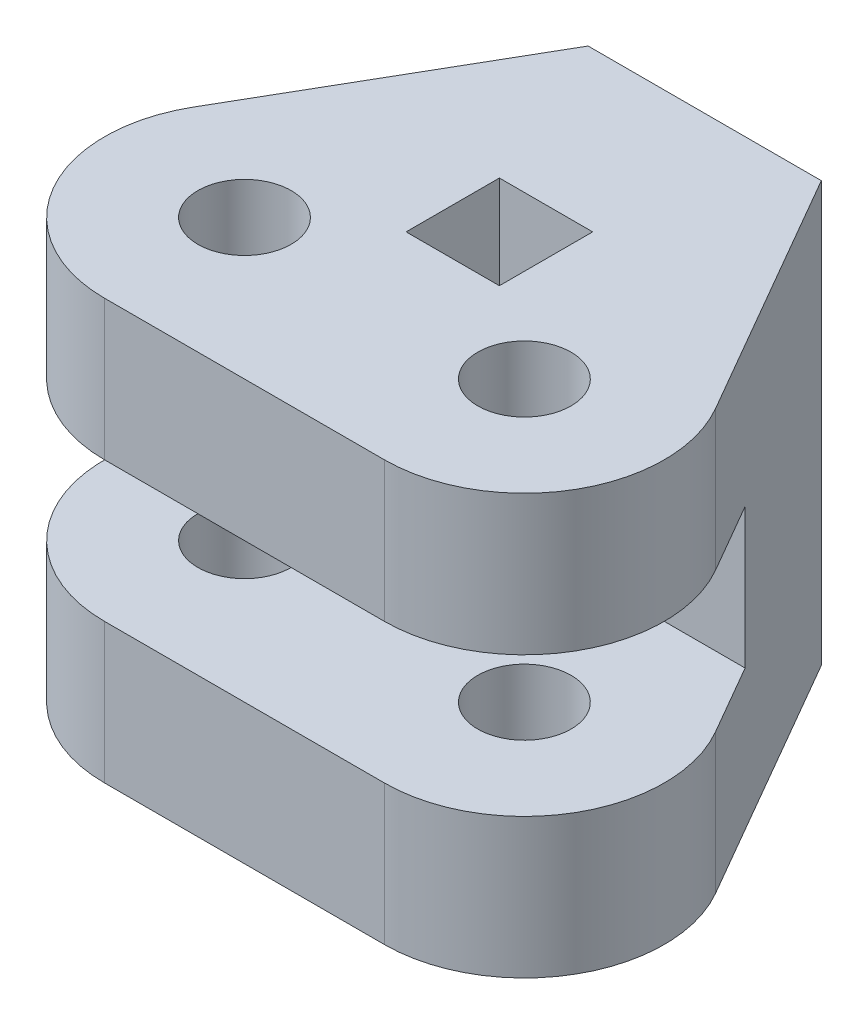
SolidWorks part; units mm, degrees
ref_plane "Alzado" through (0, 0, 0) normal (0, 0, 1) x (1, 0, 0)
ref_plane "Planta" through (0, 0, 0) normal (0, 1, 0) x (1, 0, 0)
ref_plane "Vista lateral" through (0, 0, 0) normal (1, 0, 0) x (0, 0, -1)
sketch "Croquis1" plane through (0, 0, 0) normal (0, 1, 0) x (1, 0, 0)
  line L0 (5.5981, -3.6962) -> (2.5, 1.6699)
  line L1 (-2.5, 1.6699) -> (-5.5981, -3.6962)
  line L2 (-3, -8.1962) -> (3, -8.1962)
  line L3 (0, 0) -> (-3, -5.1962) construction
  line L4 (-3, -5.1962) -> (3, -5.1962) construction
  line L5 (3, -5.1962) -> (0, 0) construction
  line L6 (8.1962, -8.1962) -> (0, 6) construction
  line L7 (-8.1962, -8.1962) -> (8.1962, -8.1962) construction
  line L8 (0, 6) -> (-8.1962, -8.1962) construction
  line L9 (-2.5, 1.6699) -> (2.5, 1.6699)
  line L10 (-1, -1.7321) -> (1, -1.7321)
  line L11 (1, -1.7321) -> (1, -3.7321)
  line L12 (1, -3.7321) -> (-1, -3.7321)
  line L13 (-1, -3.7321) -> (-1, -1.7321)
  circle A1 centre (-3, -5.1962) radius 1
  circle A2 centre (3, -5.1962) radius 1
  arc A3 (5.5981, -3.6962) -> (3, -8.1962) centre (3, -5.1962) cw
  arc A5 (-5.5981, -3.6962) -> (-3, -8.1962) centre (-3, -5.1962) ccw
  dimension "D1" = 2
  dimension "D4" = 3
  dimension "D2" = 6
  dimension "D5" = 5
  dimension "D6" = 2
  dimension "D7" = 2
  dimension "D3" = 3
extrude "Saliente-Extruir1" add sketch "Croquis1" along normal blind 9
sketch "Croquis2" plane through (0, 0, 8.1962) normal (0, 0, 1) x (1, 0, 0)
  line L0 (-3, 9) -> (3, 9) construction
  line L1 (-6, 6) -> (6, 6)
  line L2 (-6, 6) -> (-6, 3)
  line L3 (-6, 3) -> (6, 3)
  line L4 (6, 6) -> (6, 3)
  line L5 (-3, 0) -> (3, 0) construction
  line L6 (-6, 9) -> (-6, 0) construction
  line L7 (6, 0) -> (6, 9) construction
  dimension "D1" = 3
  dimension "D2" = 3
extrude "Cortar-Extruir1" cut sketch "Croquis2" against normal blind 6
sketch "Croquis3" plane through (0, 0, -1.6699) normal (0, 0, -1) x (-1, 0, 0)
  line L0 (-2.5, 0) -> (2.5, 9) construction
  line L2 (-2.5, 9) -> (2.5, 0) construction
  circle A0 centre (0, 4.5) radius 0.5
  dimension "D1" = 1
extrude "Cortar-Extruir2" cut sketch "Croquis3" against normal up to next
